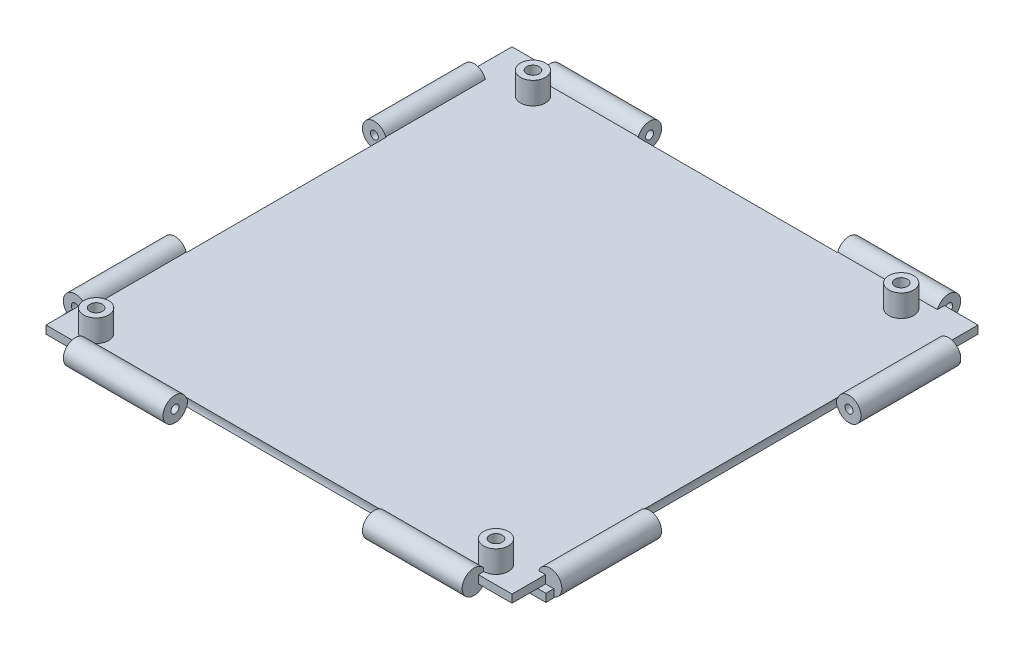
SolidWorks part; units mm, degrees
ref_plane "Front Plane" through (0, 0, 0) normal (0, 0, 1) x (1, 0, 0)
ref_plane "Top Plane" through (0, 0, 0) normal (0, 1, 0) x (1, 0, 0)
ref_plane "Right Plane" through (0, 0, 0) normal (1, 0, 0) x (0, 0, -1)
sketch "Sketch3" plane through (0, 0, 0) normal (0, 1, 0) x (1, 0, 0)
  line L1 (-48.5, -48.5) -> (48.5, -48.5)
  line L2 (-48.5, -48.5) -> (-48.5, 48.5)
  line L3 (-48.5, 48.5) -> (48.5, 48.5)
  line L4 (48.5, -48.5) -> (48.5, 48.5)
  line L5 (-48.5, -48.5) -> (48.5, 48.5) construction
  line L6 (-48.5, 48.5) -> (48.5, -48.5) construction
  point P0 (0, 0)
extrude "Boss-Extrude2" add sketch "Sketch3" along normal blind 1.6
sketch "Sketch6" plane through (0, 0, 48.5) normal (0, 0, 1) x (1, 0, 0)
  line L0 (-48.5, 1.6) -> (-48.5, 0) construction
  circle A0 centre (-47.6, 0.8) radius 2.4
  point P2 (-48.5, 0.8)
  point P5 (-48.5, 0.8)
  dimension "D1" = 0.9
  dimension "D2" = 0
extrude "Boss-Extrude3" add sketch "Sketch6" against normal blind 25
sketch "Sketch8" plane through (0, 0, 48.5) normal (0, 0, 1) x (1, 0, 0)
  line L0 (48.5, 1.6) -> (48.5, 0) construction
  line L1 (-45.3373, 0) -> (48.5, 0) construction
  circle A0 centre (47.6, 0.8) radius 2.4
  point P2 (48.5, 0.8)
  dimension "D1" = 0.9
  dimension "D2" = 0.8
extrude "Boss-Extrude4" add sketch "Sketch8" against normal blind 25
sketch "Sketch10" plane through (0, 0, -48.5) normal (0, 0, -1) x (-1, 0, 0)
  circle A0 centre (-47.6, 0.8) radius 2.4
extrude "Boss-Extrude5" add sketch "Sketch10" against normal blind 25
sketch "Sketch11" plane through (0, 0, -48.5) normal (0, 0, -1) x (-1, 0, 0)
  circle A0 centre (47.6, 0.8) radius 2.4
extrude "Boss-Extrude6" add sketch "Sketch11" against normal blind 25
sketch "Sketch12" plane through (-48.5, 0, 0) normal (-1, 0, 0) x (0, 0, 1)
  line L0 (-23.5, 3.2) -> (-48.5, 3.2) construction
  line L1 (-48.5, 3.2) -> (-48.5, -1.6) construction
  circle A0 centre (-47.6, 0.8) radius 2.4
  point P4 (-48.5, 0.8)
  dimension "D1" = 2.4
  dimension "D2" = 0.9
extrude "Boss-Extrude7" add sketch "Sketch12" against normal blind 25
sketch "Sketch13" plane through (-48.5, 0, 0) normal (-1, 0, 0) x (0, 0, 1)
  line L0 (48.5, 3.2) -> (23.5, 3.2) construction
  line L1 (48.5, -1.6) -> (48.5, 3.2) construction
  circle A0 centre (47.6, 0.8) radius 2.4
  dimension "D1" = 2.4
  dimension "D2" = 0.9
extrude "Boss-Extrude8" add sketch "Sketch13" against normal blind 25
sketch "Sketch15" plane through (48.5, 0, 0) normal (1, 0, 0) x (0, 0, -1)
  circle A0 centre (-47.6, 0.8) radius 2.4
extrude "Boss-Extrude9" add sketch "Sketch15" against normal blind 25
sketch "Sketch16" plane through (48.5, 0, 0) normal (1, 0, 0) x (0, 0, -1)
  circle A0 centre (47.6, 0.8) radius 2.4
extrude "Boss-Extrude10" add sketch "Sketch16" against normal blind 25
sketch "Sketch24" plane through (0, 0, 48.5) normal (0, 0, 1) x (1, 0, 0)
  line L1 (-45.2, -1.9741) -> (-50, -1.9741)
  line L2 (-45.2, -1.9741) -> (-45.2, 3.5741)
  line L3 (-45.2, 3.5741) -> (-50, 3.5741)
  line L4 (-50, -1.9741) -> (-50, 3.5741)
  line L5 (-45.2, -1.9741) -> (-50, 3.5741) construction
  line L6 (-45.2, 3.5741) -> (-50, -1.9741) construction
  point P0 (-47.6, 0.8)
extrude "Cut-Extrude6" cut sketch "Sketch24" against normal blind 3.3
sketch "Sketch25" plane through (0, 0, 48.5) normal (0, 0, -1) x (-1, 0, 0)
  line L1 (50, -1.6) -> (45.2, -1.6)
  line L2 (50, -1.6) -> (50, 3.2)
  line L3 (50, 3.2) -> (45.2, 3.2)
  line L4 (45.2, -1.6) -> (45.2, 3.2)
  line L5 (50, -1.6) -> (45.2, 3.2) construction
  line L6 (50, 3.2) -> (45.2, -1.6) construction
  point P0 (47.6, 0.8)
extrude "Cut-Extrude7" cut sketch "Sketch25" against normal blind 3.3
sketch "Sketch27" plane through (0, 0, -48.5) normal (0, 0, -1) x (-1, 0, 0)
  line L1 (45.2, -1.7788) -> (50, -1.7788)
  line L2 (45.2, -1.7788) -> (45.2, 3.3788)
  line L3 (45.2, 3.3788) -> (50, 3.3788)
  line L4 (50, -1.7788) -> (50, 3.3788)
  line L5 (45.2, -1.7788) -> (50, 3.3788) construction
  line L6 (45.2, 3.3788) -> (50, -1.7788) construction
  point P0 (47.6, 0.8)
extrude "Cut-Extrude8" cut sketch "Sketch27" against normal blind 3.3
sketch "Sketch28" plane through (0, 0, -45.2) normal (0, 0, -1) x (-1, 0, 0)
  line L1 (50, -1.6) -> (45.2, -1.6)
  line L2 (50, -1.6) -> (50, 3.2)
  line L3 (50, 3.2) -> (45.2, 3.2)
  line L4 (45.2, -1.6) -> (45.2, 3.2)
  line L5 (50, -1.6) -> (45.2, 3.2) construction
  line L6 (50, 3.2) -> (45.2, -1.6) construction
  point P0 (47.6, 0.8)
extrude "Cut-Extrude9" cut sketch "Sketch28" along normal blind 6
sketch "Sketch29" plane through (0, 0, 48.5) normal (0, 0, 1) x (1, 0, 0)
  line L1 (45.2, -1.9133) -> (50, -1.9133)
  line L2 (45.2, -1.9133) -> (45.2, 3.5133)
  line L3 (45.2, 3.5133) -> (50, 3.5133)
  line L4 (50, -1.9133) -> (50, 3.5133)
  line L5 (45.2, -1.9133) -> (50, 3.5133) construction
  line L6 (45.2, 3.5133) -> (50, -1.9133) construction
  point P0 (47.6, 0.8)
extrude "Cut-Extrude10" cut sketch "Sketch29" against normal blind 3.3
sketch "Sketch30" plane through (0, 0, 48.5) normal (0, 0, -1) x (-1, 0, 0)
  line L1 (-45.2, 3.2) -> (-50.2988, 3.2)
  line L2 (-45.2, 3.2) -> (-45.2, -1.6)
  line L3 (-45.2, -1.6) -> (-50.2988, -1.6)
  line L4 (-50.2988, 3.2) -> (-50.2988, -1.6)
extrude "Cut-Extrude11" cut sketch "Sketch30" against normal blind 3.3
sketch "Sketch31" plane through (0, 0, -48.5) normal (0, 0, -1) x (-1, 0, 0)
  line L1 (-45.2, -1.9404) -> (-50, -1.9404)
  line L2 (-45.2, -1.9404) -> (-45.2, 3.5404)
  line L3 (-45.2, 3.5404) -> (-50, 3.5404)
  line L4 (-50, -1.9404) -> (-50, 3.5404)
  line L5 (-45.2, -1.9404) -> (-50, 3.5404) construction
  line L6 (-45.2, 3.5404) -> (-50, -1.9404) construction
  point P0 (-47.6, 0.8)
extrude "Cut-Extrude12" cut sketch "Sketch31" against normal blind 3.3
sketch "Sketch32" plane through (0, 0, -48.5) normal (0, 0, 1) x (1, 0, 0)
  line L1 (45.2, 3.2) -> (50.1875, 3.2)
  line L2 (45.2, 3.2) -> (45.2, -1.6)
  line L3 (45.2, -1.6) -> (50.1875, -1.6)
  line L4 (50.1875, 3.2) -> (50.1875, -1.6)
extrude "Cut-Extrude13" cut sketch "Sketch32" against normal blind 3.3
sketch "Sketch38" plane through (0, 0, -23.5) normal (0, 0, 1) x (1, 0, 0)
  circle A0 centre (-47.6, 0.8) radius 2.4
extrude "Boss-Extrude11" add sketch "Sketch38" along normal blind 1
sketch "Sketch39" plane through (0, 0, 23.5) normal (0, 0, -1) x (-1, 0, 0)
  circle A0 centre (47.6, 0.8) radius 2.4
extrude "Boss-Extrude12" add sketch "Sketch39" along normal blind 1
sketch "Sketch42" plane through (0, 0, -23.5) normal (0, 0, 1) x (1, 0, 0)
  circle A0 centre (47.6, 0.8) radius 2.4
extrude "Boss-Extrude13" add sketch "Sketch42" along normal blind 1
sketch "Sketch43" plane through (0, 0, 23.5) normal (0, 0, -1) x (-1, 0, 0)
  circle A0 centre (-47.6, 0.8) radius 2.4
extrude "Boss-Extrude14" add sketch "Sketch43" along normal blind 1
sketch "Sketch44" plane through (23.5, 0, 0) normal (-1, 0, 0) x (0, 0, 1)
  circle A0 centre (-47.6, 0.8) radius 2.4
extrude "Boss-Extrude15" add sketch "Sketch44" along normal blind 1
sketch "Sketch45" plane through (-23.5, 0, 0) normal (1, 0, 0) x (0, 0, -1)
  circle A0 centre (47.6, 0.8) radius 2.4
extrude "Boss-Extrude16" add sketch "Sketch45" along normal blind 1
sketch "Sketch46" plane through (23.5, 0, 0) normal (-1, 0, 0) x (0, 0, 1)
  circle A0 centre (47.6, 0.8) radius 2.4
extrude "Boss-Extrude17" add sketch "Sketch46" along normal blind 1
sketch "Sketch47" plane through (-23.5, 0, 0) normal (1, 0, 0) x (0, 0, -1)
  circle A0 centre (-47.6, 0.8) radius 2.4
extrude "Boss-Extrude18" add sketch "Sketch47" along normal blind 1
sketch "Sketch69" plane through (0, 0, 45.2) normal (0, 0, 1) x (1, 0, 0)
  line L0 (-45.3373, 1.6) -> (-46.7373, 1.6)
  line L1 (-46.7373, 1.6) -> (-46.7373, 0)
  line L2 (-46.7373, 0) -> (-45.3373, 0)
  line L3 (-45.3373, 0) -> (-45.3373, -2.2963)
  line L4 (-45.3373, -2.2963) -> (-50.8618, -2.2963)
  line L5 (-50.8618, -2.2963) -> (-50.8618, 4.0891)
  line L6 (-50.8618, 4.0891) -> (-45.3373, 4.0891)
  line L7 (-45.3373, 4.0891) -> (-45.3373, 1.6)
extrude "Cut-Extrude24" cut sketch "Sketch69" against normal blind 5.2
sketch "Sketch72" plane through (0, 0, 45.2) normal (0, 0, 1) x (1, 0, 0)
  line L0 (45.3373, 1.6) -> (46.7373, 1.6)
  line L1 (46.7373, 1.6) -> (46.7373, 0)
  line L2 (46.7373, 0) -> (45.3373, 0)
  line L3 (45.3373, 0) -> (45.3373, -2.332)
  line L4 (45.3373, -2.332) -> (51.5664, -2.332)
  line L5 (51.5664, -2.332) -> (51.5664, 3.8868)
  line L6 (51.5664, 3.8868) -> (45.3373, 3.8868)
  line L7 (45.3373, 3.8868) -> (45.3373, 1.6)
extrude "Cut-Extrude25" cut sketch "Sketch72" against normal blind 5.2
sketch "Sketch74" plane through (0, 0, -45.2) normal (0, 0, -1) x (-1, 0, 0)
  line L0 (-45.3373, 1.6) -> (-46.7373, 1.6)
  line L1 (-46.7373, 1.6) -> (-46.7373, 0)
  line L2 (-46.7373, 0) -> (-45.3373, 0)
  line L3 (-45.3373, 0) -> (-45.3373, -2.1525)
  line L4 (-45.3373, -2.1525) -> (-50.4022, -2.1525)
  line L5 (-50.4022, -2.1525) -> (-50.4022, 3.9519)
  line L6 (-50.4022, 3.9519) -> (-45.3373, 3.9519)
  line L7 (-45.3373, 3.9519) -> (-45.3373, 1.6)
extrude "Cut-Extrude26" cut sketch "Sketch74" against normal blind 5.2
sketch "Sketch75" plane through (0, 0, -45.2) normal (0, 0, -1) x (-1, 0, 0)
  line L0 (45.3373, 1.6) -> (46.7373, 1.6)
  line L1 (46.7373, 1.6) -> (46.7373, 0)
  line L2 (46.7373, 0) -> (45.3373, 0)
  line L3 (45.3373, 0) -> (45.3373, -1.8864)
  line L4 (45.3373, -1.8864) -> (51.292, -1.8864)
  line L5 (51.292, -1.8864) -> (51.292, 3.8238)
  line L6 (51.292, 3.8238) -> (45.3373, 3.8238)
  line L7 (45.3373, 3.8238) -> (45.3373, 1.6)
extrude "Cut-Extrude27" cut sketch "Sketch75" against normal blind 5.2
sketch "Sketch77" plane through (-45.2, 0, 0) normal (-1, 0, 0) x (0, 0, 1)
  line L0 (-45.3373, 1.6) -> (-45.3373, 4.0728)
  line L1 (-45.3373, 4.0728) -> (-50.7539, 4.0728)
  line L2 (-50.7539, 4.0728) -> (-50.7539, -2.0737)
  line L3 (-50.7539, -2.0737) -> (-45.3373, -2.0737)
  line L4 (-45.3373, -2.0737) -> (-45.3373, 0)
  line L5 (-45.3373, 0) -> (-46.7373, 0)
  line L6 (-46.7373, 0) -> (-46.7373, 1.6)
  line L7 (-46.7373, 1.6) -> (-45.3373, 1.6)
extrude "Cut-Extrude29" cut sketch "Sketch77" against normal blind 5.2
sketch "Sketch78" plane through (-45.2, 0, 0) normal (-1, 0, 0) x (0, 0, 1)
  line L0 (45.3373, 1.6) -> (45.3373, 3.5518)
  line L1 (45.3373, 3.5518) -> (50.6981, 3.5518)
  line L2 (50.6981, 3.5518) -> (50.6981, -1.7977)
  line L3 (50.6981, -1.7977) -> (45.3373, -1.7977)
  line L4 (45.3373, -1.7977) -> (45.3373, 0)
  line L5 (45.3373, 0) -> (46.7373, 0)
  line L6 (46.7373, 0) -> (46.7373, 1.6)
  line L7 (46.7373, 1.6) -> (45.3373, 1.6)
extrude "Cut-Extrude30" cut sketch "Sketch78" against normal blind 5.2
sketch "Sketch79" plane through (45.2, 0, 0) normal (1, 0, 0) x (0, 0, -1)
  line L0 (-45.3373, 1.6) -> (-45.3373, 4.0003)
  line L1 (-45.3373, 4.0003) -> (-50.7843, 4.0003)
  line L2 (-50.7843, 4.0003) -> (-50.7843, -1.8519)
  line L3 (-50.7843, -1.8519) -> (-45.3373, -1.8519)
  line L4 (-45.3373, -1.8519) -> (-45.3373, 0)
  line L5 (-45.3373, 0) -> (-46.7373, 0)
  line L6 (-46.7373, 0) -> (-46.7373, 1.6)
  line L7 (-46.7373, 1.6) -> (-45.3373, 1.6)
extrude "Cut-Extrude31" cut sketch "Sketch79" against normal blind 5.2
sketch "Sketch80" plane through (45.2, 0, 0) normal (1, 0, 0) x (0, 0, -1)
  line L0 (45.3373, 1.6) -> (45.3373, 3.7938)
  line L1 (45.3373, 3.7938) -> (50.5196, 3.7938)
  line L2 (50.5196, 3.7938) -> (50.5196, -2.0451)
  line L3 (50.5196, -2.0451) -> (45.3373, -2.0451)
  line L4 (45.3373, -2.0451) -> (45.3373, 0)
  line L5 (45.3373, 0) -> (46.7373, 0)
  line L6 (46.7373, 0) -> (46.7373, 1.6)
  line L7 (46.7373, 1.6) -> (45.3373, 1.6)
extrude "Cut-Extrude32" cut sketch "Sketch80" against normal blind 5.2
sketch "Sketch81" plane through (0, 1.6, 0) normal (0, 1, 0) x (1, 0, 0)
  line L1 (-45.2, 46.7373) -> (-46.7373, 46.7373)
  line L2 (-45.2, 46.7373) -> (-45.2, 45.2)
  line L3 (-45.2, 45.2) -> (-46.7373, 45.2)
  line L4 (-46.7373, 46.7373) -> (-46.7373, 45.2)
extrude "Boss-Extrude21" add sketch "Sketch81" against normal blind 1.6
sketch "Sketch82" plane through (0, 1.6, 0) normal (0, 1, 0) x (1, 0, 0)
  line L1 (45.2, 46.7373) -> (46.7373, 46.7373)
  line L2 (45.2, 46.7373) -> (45.2, 45.2)
  line L3 (45.2, 45.2) -> (46.7373, 45.2)
  line L4 (46.7373, 46.7373) -> (46.7373, 45.2)
extrude "Boss-Extrude22" add sketch "Sketch82" against normal blind 1.6
sketch "Sketch83" plane through (0, 1.6, 0) normal (0, 1, 0) x (1, 0, 0)
  line L1 (-46.7373, -45.2) -> (-45.2, -45.2)
  line L2 (-46.7373, -45.2) -> (-46.7373, -46.7373)
  line L3 (-46.7373, -46.7373) -> (-45.2, -46.7373)
  line L4 (-45.2, -45.2) -> (-45.2, -46.7373)
extrude "Boss-Extrude23" add sketch "Sketch83" against normal blind 1.6
sketch "Sketch84" plane through (0, 1.6, 0) normal (0, 1, 0) x (1, 0, 0)
  line L1 (46.7373, -45.2) -> (45.2, -45.2)
  line L2 (46.7373, -45.2) -> (46.7373, -46.7373)
  line L3 (46.7373, -46.7373) -> (45.2, -46.7373)
  line L4 (45.2, -45.2) -> (45.2, -46.7373)
extrude "Boss-Extrude24" add sketch "Sketch84" against normal blind 1.6
sketch "Sketch87" plane through (-22.5, 0, 0) normal (1, 0, 0) x (0, 0, -1)
  circle A0 centre (-47.6, 0.8) radius 2.4
extrude "Boss-Extrude25" add sketch "Sketch87" along normal blind 2.5
sketch "Sketch88" plane through (22.5, 0, 0) normal (-1, 0, 0) x (0, 0, 1)
  circle A0 centre (47.6, 0.8) radius 2.4
extrude "Boss-Extrude26" add sketch "Sketch88" along normal blind 2.5
sketch "Sketch91" plane through (-20, 0, 0) normal (1, 0, 0) x (0, 0, -1)
  circle A0 centre (-47.6, 0.8) radius 2.5
extrude "Cut-Extrude33" cut sketch "Sketch91" along normal blind 40
sketch "Sketch93" plane through (0, 0, -22.5) normal (0, 0, 1) x (1, 0, 0)
  circle A0 centre (-47.6, 0.8) radius 2.4
extrude "Boss-Extrude27" add sketch "Sketch93" along normal blind 2.5
sketch "Sketch94" plane through (0, 0, 22.5) normal (0, 0, -1) x (-1, 0, 0)
  circle A0 centre (47.6, 0.8) radius 2.4
extrude "Boss-Extrude28" add sketch "Sketch94" along normal blind 2.5
sketch "Sketch97" plane through (0, 0, -20) normal (0, 0, 1) x (1, 0, 0)
  circle A0 centre (-47.6, 0.8) radius 2.5
extrude "Cut-Extrude34" cut sketch "Sketch97" along normal blind 40
sketch "Sketch98" plane through (0, 0, -22.5) normal (0, 0, 1) x (1, 0, 0)
  circle A0 centre (47.6, 0.8) radius 2.4
extrude "Boss-Extrude29" add sketch "Sketch98" along normal blind 2.5
sketch "Sketch99" plane through (0, 0, 22.5) normal (0, 0, -1) x (-1, 0, 0)
  circle A0 centre (-47.6, 0.8) radius 2.4
extrude "Boss-Extrude30" add sketch "Sketch99" along normal blind 2.5
sketch "Sketch100" plane through (0, 0, -20) normal (0, 0, 1) x (1, 0, 0)
  circle A0 centre (47.6, 0.8) radius 2.5
extrude "Cut-Extrude35" cut sketch "Sketch100" along normal blind 40
sketch "Sketch101" plane through (-22.5, 0, 0) normal (1, 0, 0) x (0, 0, -1)
  circle A0 centre (47.6, 0.8) radius 2.4
extrude "Boss-Extrude31" add sketch "Sketch101" along normal blind 2.5
sketch "Sketch102" plane through (22.5, 0, 0) normal (-1, 0, 0) x (0, 0, 1)
  circle A0 centre (-47.6, 0.8) radius 2.4
extrude "Boss-Extrude32" add sketch "Sketch102" along normal blind 2.5
sketch "Sketch104" plane through (-20, 0, 0) normal (1, 0, 0) x (0, 0, -1)
  circle A0 centre (47.6, 0.8) radius 2.5
extrude "Cut-Extrude36" cut sketch "Sketch104" along normal blind 40
sketch "Sketch105" plane through (0, 0, 40) normal (0, 0, 1) x (1, 0, 0)
  circle A0 centre (-47.6, 0.8) radius 0.81
extrude "Cut-Extrude37" cut sketch "Sketch105" against normal blind 78.5
sketch "Sketch106" plane through (-40, 0, 0) normal (-1, 0, 0) x (0, 0, 1)
  circle A0 centre (47.6, 0.8) radius 0.81
extrude "Cut-Extrude38" cut sketch "Sketch106" against normal blind 78.5
sketch "Sketch107" plane through (40, 0, 0) normal (1, 0, 0) x (0, 0, -1)
  circle A0 centre (47.6, 0.8) radius 0.81
extrude "Cut-Extrude39" cut sketch "Sketch107" against normal blind 78.5
sketch "Sketch108" plane through (0, 0, -40) normal (0, 0, -1) x (-1, 0, 0)
  circle A0 centre (-47.6, 0.8) radius 0.81
extrude "Cut-Extrude40" cut sketch "Sketch108" against normal blind 78.5
sketch "Sketch135" plane through (0, 1.6, 0) normal (0, 1, 0) x (1, 0, 0)
  line L2 (28.1604, 35.2315) -> (0, 7.0711)
  line L3 (0, 7.0711) -> (-28.1604, 35.2315)
  line L4 (-28.1604, 35.2315) -> (28.1604, 35.2315)
  line L5 (-20, 45.2315) -> (20, 45.2315) construction
  dimension "D1" = 10
extrude "Cut-Extrude47" cut sketch "Sketch135" against normal blind 20
sketch "Sketch136" plane through (0, 1.6, 0) normal (0, 1, 0) x (1, 0, 0)
  line L2 (-28.1604, -35.2315) -> (0, -7.0711)
  line L3 (0, -7.0711) -> (28.1604, -35.2315)
  line L4 (28.1604, -35.2315) -> (-28.1604, -35.2315)
  line L5 (20, -45.2315) -> (-20, -45.2315) construction
  dimension "D3" = 10
extrude "Cut-Extrude48" cut sketch "Sketch136" against normal blind 20
sketch "Sketch137" plane through (0, 1.6, 0) normal (0, 1, 0) x (1, 0, 0)
  line L0 (35.2315, 28.1604) -> (7.0711, 0)
  line L1 (7.0711, 0) -> (35.2315, -28.1604)
  line L2 (35.2315, -28.1604) -> (35.2315, 28.1604)
  line L3 (0, 7.0711) -> (28.1604, 35.2315) construction
  line L4 (28.1604, -35.2315) -> (0, -7.0711) construction
  line L5 (45.2315, 20) -> (45.2315, -20) construction
  dimension "D1" = 10
  dimension "D2" = 10
  dimension "D3" = 10
extrude "Cut-Extrude49" cut sketch "Sketch137" against normal blind 20
sketch "Sketch138" plane through (0, 1.6, 0) normal (0, 1, 0) x (1, 0, 0)
  line L0 (-35.2315, 28.1604) -> (-7.0711, 0)
  line L1 (-7.0711, 0) -> (-35.2315, -28.1604)
  line L2 (-35.2315, -28.1604) -> (-35.2315, 28.1604)
  line L3 (-45.2315, -20) -> (-45.2315, 20) construction
  line L4 (0, -7.0711) -> (-28.1604, -35.2315) construction
  line L5 (-28.1604, 35.2315) -> (0, 7.0711) construction
  dimension "D1" = 10
  dimension "D2" = 10
  dimension "D3" = 10
extrude "Cut-Extrude50" cut sketch "Sketch138" against normal blind 20
sketch "Sketch139" plane through (0, 1.6, 0) normal (0, 1, 0) x (1, 0, 0)
  circle A0 centre (0, 0) radius 15
extrude "Boss-Extrude40" add sketch "Sketch139" against normal blind 1.6
sketch "Sketch140" plane through (0, 1.6, 0) normal (0, 1, 0) x (1, 0, 0)
  circle A0 centre (0, 0) radius 5
extrude "Cut-Extrude51" cut sketch "Sketch140" against normal blind 1.6
fillet "Fillet7" radius 2 16 edges at (28.1604, 0.8, -35.2315) (35.2315, 0.8, -28.1604) (35.2315, 0.8, 28.1604) (28.1604, 0.8, 35.2315) (-28.1604, 0.8, 35.2315) (-13.5355, 0.8, -6.4645) (-13.5355, 0.8, 6.4645) (-35.2315, 0.8, 28.1604) (6.4645, 0.8, -13.5355) (-6.4645, 0.8, -13.5355) (13.5355, 0.8, 6.4645) (13.5355, 0.8, -6.4645) (-6.4645, 0.8, 13.5355) (6.4645, 0.8, 13.5355) (-35.2315, 0.8, -28.1604) (-28.1604, 0.8, -35.2315)
sketch "Sketch119" plane through (0, 1.6, 0) normal (0, 1, 0) x (1, 0, 0)
  line L2 (-28.1604, 35.2315) -> (28.1604, 35.2315)
  line L3 (28.1604, 35.2315) -> (0, 7.0711)
  line L4 (0, 7.0711) -> (-28.1604, 35.2315)
  line L5 (-20, 45.2315) -> (20, 45.2315) construction
  dimension "D1" = 10
extrude "Cut-Extrude41" cut sketch "Sketch119" against normal blind 1.6
sketch "Sketch120" plane through (0, 1.6, 0) normal (0, 1, 0) x (1, 0, 0)
  line L2 (-28.1604, -35.2315) -> (28.1604, -35.2315)
  line L3 (28.1604, -35.2315) -> (0, -7.0711)
  line L4 (-28.1604, -35.2315) -> (0, -7.0711)
  line L5 (20, -45.2315) -> (-20, -45.2315) construction
  dimension "D3" = 10
extrude "Cut-Extrude42" cut sketch "Sketch120" against normal blind 1.6
sketch "Sketch121" plane through (0, 1.6, 0) normal (0, 1, 0) x (1, 0, 0)
  line L0 (-35.2315, 28.1604) -> (-35.2315, -28.1604)
  line L1 (-35.2315, -28.1604) -> (-7.0711, 0)
  line L2 (-35.2315, 28.1604) -> (-7.0711, 0)
  line L3 (-28.1604, 35.2315) -> (0, 7.0711) construction
  line L4 (0, -7.0711) -> (-28.1604, -35.2315) construction
  line L5 (-45.2315, -20) -> (-45.2315, 20) construction
  dimension "D1" = 10
  dimension "D2" = 10
  dimension "D3" = 10
extrude "Cut-Extrude43" cut sketch "Sketch121" against normal blind 1.6
sketch "Sketch122" plane through (0, 1.6, 0) normal (0, 1, 0) x (1, 0, 0)
  line L0 (35.2315, 28.1604) -> (35.2315, -28.1604)
  line L1 (35.2315, -28.1604) -> (7.0711, 0)
  line L2 (35.2315, 28.1604) -> (7.0711, 0)
  line L3 (0, 7.0711) -> (28.1604, 35.2315) construction
  line L4 (28.1604, -35.2315) -> (0, -7.0711) construction
  line L5 (45.2315, 20) -> (45.2315, -20) construction
  dimension "D1" = 10
  dimension "D2" = 10
  dimension "D3" = 10
extrude "Cut-Extrude44" cut sketch "Sketch122" against normal blind 1.6
sketch "Sketch123" plane through (0, 1.6, 0) normal (0, 1, 0) x (1, 0, 0)
  circle A0 centre (0, 0) radius 15
extrude "Boss-Extrude35" add sketch "Sketch123" against normal blind 1.6
sketch "Sketch124" plane through (0, 1.6, 0) normal (0, 1, 0) x (1, 0, 0)
  circle A0 centre (0, 0) radius 5
extrude "Cut-Extrude45" cut sketch "Sketch124" against normal blind 1.6
fillet "Fillet4" radius 2 16 edges at (35.2315, 0.8, 28.1604) (35.2315, 0.8, -28.1604) (-6.4645, 0.8, 13.5355) (6.4645, 0.8, 13.5355) (28.1604, 0.8, 35.2315) (13.5355, 0.8, -6.4645) (13.5355, 0.8, 6.4645) (-28.1604, 0.8, 35.2315) (-13.5355, 0.8, 6.4645) (-13.5355, 0.8, -6.4645) (28.1604, 0.8, -35.2315) (-28.1604, 0.8, -35.2315) (6.4645, 0.8, -13.5355) (-6.4645, 0.8, -13.5355) (-35.2315, 0.8, 28.1604) (-35.2315, 0.8, -28.1604)
sketch "Sketch144" plane through (0, 0, -46.7373) normal (0, 0, -1) x (-1, 0, 0)
  line L1 (46.7373, 1.6) -> (40, 1.6)
  line L2 (46.7373, 1.6) -> (46.7373, 0)
  line L3 (46.7373, 0) -> (40, 0)
  line L4 (40, 1.6) -> (40, 0)
extrude "Boss-Extrude42" add sketch "Sketch144" along normal blind 1.6
sketch "Sketch145" plane through (-46.7373, 0, 0) normal (-1, 0, 0) x (0, 0, 1)
  line L1 (-48.3373, 1.6) -> (-40, 1.6)
  line L2 (-48.3373, 1.6) -> (-48.3373, 0)
  line L3 (-48.3373, 0) -> (-40, 0)
  line L4 (-40, 1.6) -> (-40, 0)
extrude "Boss-Extrude43" add sketch "Sketch145" along normal blind 1.6
sketch "Sketch147" plane through (0, 0, 0) normal (0, -1, 0) x (1, 0, 0)
  line L0 (-40, -40) -> (-48.4, -40)
  line L1 (-50, -40) -> (-45.3373, -40) construction
  line L2 (-48.4, -40) -> (-48.4, -41.6)
  line L3 (-48.4, -41.6) -> (-40, -41.6)
  line L4 (-40, -41.6) -> (-40, -40)
  line L5 (-40, -45.3373) -> (-40, -48.3373) construction
  dimension "D1" = 1.6
  dimension "D2" = 8.4
  dimension "D3" = 0
extrude "Boss-Extrude44" add sketch "Sketch147" along normal blind 1.6
sketch "Sketch149" plane through (0, 0, 0) normal (0, -1, 0) x (1, 0, 0)
  line L0 (-45.3373, 40) -> (-50, 40) construction
  line L1 (-48.4, 40) -> (-40, 40)
  line L3 (-48.4, 40) -> (-48.4, 41.6)
  line L4 (-48.4, 41.6) -> (-40, 41.6)
  line L6 (-40, 40) -> (-40, 41.6)
  line L7 (-40, 50) -> (-40, 45.3373) construction
  dimension "D1" = 1.6
  dimension "D2" = 0
  dimension "D3" = 8.4
extrude "Boss-Extrude45" add sketch "Sketch149" along normal blind 1.6
sketch "Sketch150" plane through (0, 0, 0) normal (0, -1, 0) x (1, 0, 0)
  line L0 (45.3373, -40) -> (50, -40) construction
  line L1 (48.4, -40) -> (40, -40)
  line L2 (48.4, -40) -> (48.4, -41.6)
  line L3 (48.4, -41.6) -> (40, -41.6)
  line L4 (40, -40) -> (40, -41.6)
  dimension "D1" = 1.6
  dimension "D2" = 8.4
extrude "Boss-Extrude46" add sketch "Sketch150" along normal blind 1.6
sketch "Sketch151" plane through (0, 0, 0) normal (0, -1, 0) x (1, 0, 0)
  line L0 (40, 45.3373) -> (40, 50) construction
  line L1 (40, 41.6) -> (48.4, 41.6)
  line L2 (40, 41.6) -> (40, 40)
  line L3 (40, 40) -> (48.4, 40)
  line L4 (48.4, 41.6) -> (48.4, 40)
  line L5 (50, 40) -> (45.3373, 40) construction
  dimension "D1" = 1.6
  dimension "D2" = 8.4
extrude "Boss-Extrude47" add sketch "Sketch151" along normal blind 1.6
fillet "Fillet12" radius 1 4 edges at (40, -0.8, 40) (40, -0.8, -40) (-40, -0.8, -40) (-40, -0.8, 40)
sketch "Sketch162" plane through (0, 1.6, 0) normal (0, 1, 0) x (1, 0, 0)
  circle A0 centre (36.15, 41.92) radius 2.5
  dimension "D1" = 36.15
  dimension "D2" = 41.92
extrude "Boss-Extrude53" add sketch "Sketch162" along normal blind 4.45
sketch "Sketch163" plane through (0, 1.6, 0) normal (0, 1, 0) x (1, 0, 0)
  circle A0 centre (-40.25, -43.17) radius 2.5
  dimension "D1" = 43.17
  dimension "D2" = 40.25
extrude "Boss-Extrude54" add sketch "Sketch163" along normal blind 4.45
sketch "Sketch164" plane through (0, 1.6, 0) normal (0, 1, 0) x (1, 0, 0)
  circle A0 centre (39.96, -43.17) radius 2.5
  dimension "D1" = 39.96
  dimension "D2" = 43.17
extrude "Boss-Extrude55" add sketch "Sketch164" along normal blind 4.45
sketch "Sketch172" plane through (0, 1.6, 0) normal (0, 1, 0) x (1, 0, 0)
  line L0 (-35.2315, 23.332) -> (-35.2315, -23.332) construction
  line L1 (-20, 45.2315) -> (20, 45.2315) construction
  circle A0 centre (-37.71, 41.92) radius 2.5
  point P2 (-35.2315, 0)
  point P5 (0, 45.2315)
  dimension "D1" = 41.92
  dimension "D2" = 37.71
extrude "Boss-Extrude57" add sketch "Sketch172" along normal blind 4.45
hole_wizard "M3x0.5 Tapped Hole2" positions "Sketch174" profile "Sketch173" tap size "M3x0.5" standard "ANSI Metric"
sketch "Sketch174" plane through (0, 6.05, 0) normal (0, 1, 0) x (1, 0, 0)
  point P0 (-37.71, 41.92)
  point P3 (36.15, 41.92)
  point P6 (39.96, -43.17)
  point P9 (-40.25, -43.17)
sketch "Sketch173" plane through (-37.71, 6.05, -41.92) normal (1, 0, 0) x (0, 0, 1)
  line L0 (0, 0) -> (0, 5.2011)
  line L1 (0, 5.2011) -> (1.25, 4.45)
  line L2 (1.25, 4.45) -> (1.25, 0)
  line L5 (1.25, 0) -> (0, 0)
  line L10 (0, 5.2011) -> (-1.25, 4.45) construction
  line L11 (0, -6.35) -> (0, 107.95) construction
  dimension "Tap Drill Dia." = 2.5
  dimension "Tap Drill Depth" = 4.45
  dimension "Drill Angle" = 118
cosmetic thread "Hole Thread5" parameters "D1"=4.45, "D2"=3
cosmetic thread "Hole Thread6" parameters "D1"=4.45, "D2"=3
cosmetic thread "Hole Thread7" parameters "D1"=4.45, "D2"=3
cosmetic thread "Hole Thread8" parameters "D1"=4.45, "D2"=3
sketch "Sketch176" plane through (0, 0, 0) normal (0, -1, 0) x (1, 0, 0)
  line L1 (-42.4946, -44.8554) -> (42.4946, -44.8554)
  line L2 (-42.4946, -44.8554) -> (-42.4946, 44.8554)
  line L3 (-42.4946, 44.8554) -> (42.4946, 44.8554)
  line L4 (42.4946, -44.8554) -> (42.4946, 44.8554)
  line L5 (-42.4946, -44.8554) -> (42.4946, 44.8554) construction
  line L6 (-42.4946, 44.8554) -> (42.4946, -44.8554) construction
  point P0 (0, 0)
extrude "Boss-Extrude58" add sketch "Sketch176" against normal blind 1.6
